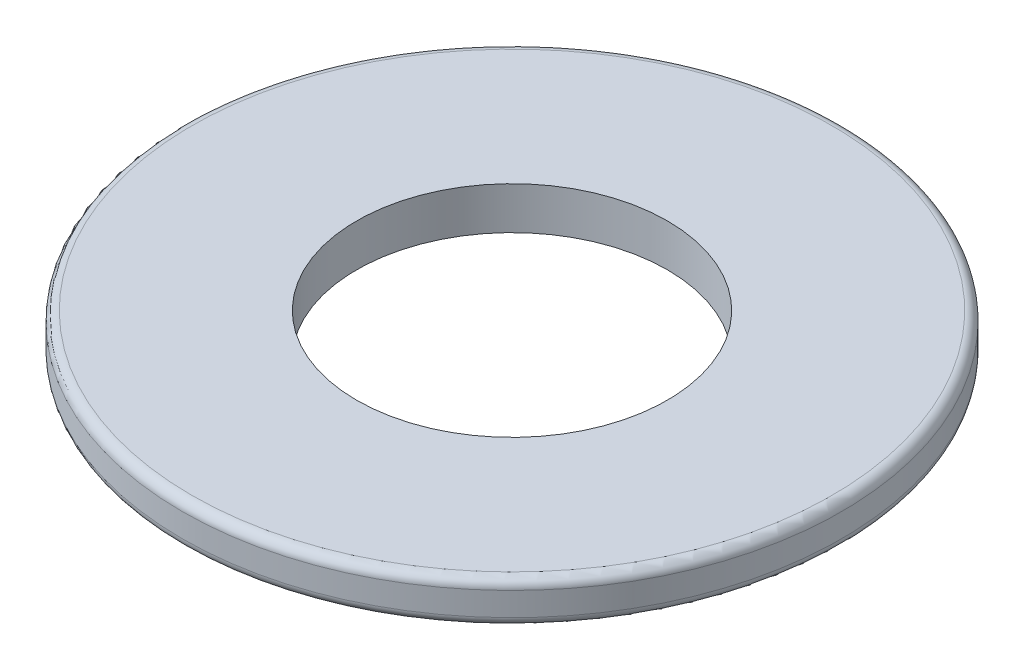
SolidWorks part; units mm, degrees
ref_plane "Front" through (0, 0, 0) normal (0, 0, 1) x (1, 0, 0)
ref_plane "Top" through (0, 0, 0) normal (0, 1, 0) x (1, 0, 0)
ref_plane "Right" through (0, 0, 0) normal (1, 0, 0) x (0, 0, -1)
sketch "Sketch2" plane through (0, 0, 0) normal (0, 1, 0) x (1, 0, 0)
  circle A0 centre (0, 0) radius 3.5
  circle A1 centre (0, 0) radius 1.65
  dimension "D1" = 7
  dimension "D2" = 3.3
extrude "Boss-Extrude1" add sketch "Sketch2" along normal blind 0.45
fillet "Fillet1" radius 0.1 2 edges at (0, 0, 3.5) (0, 0.45, 3.5)
